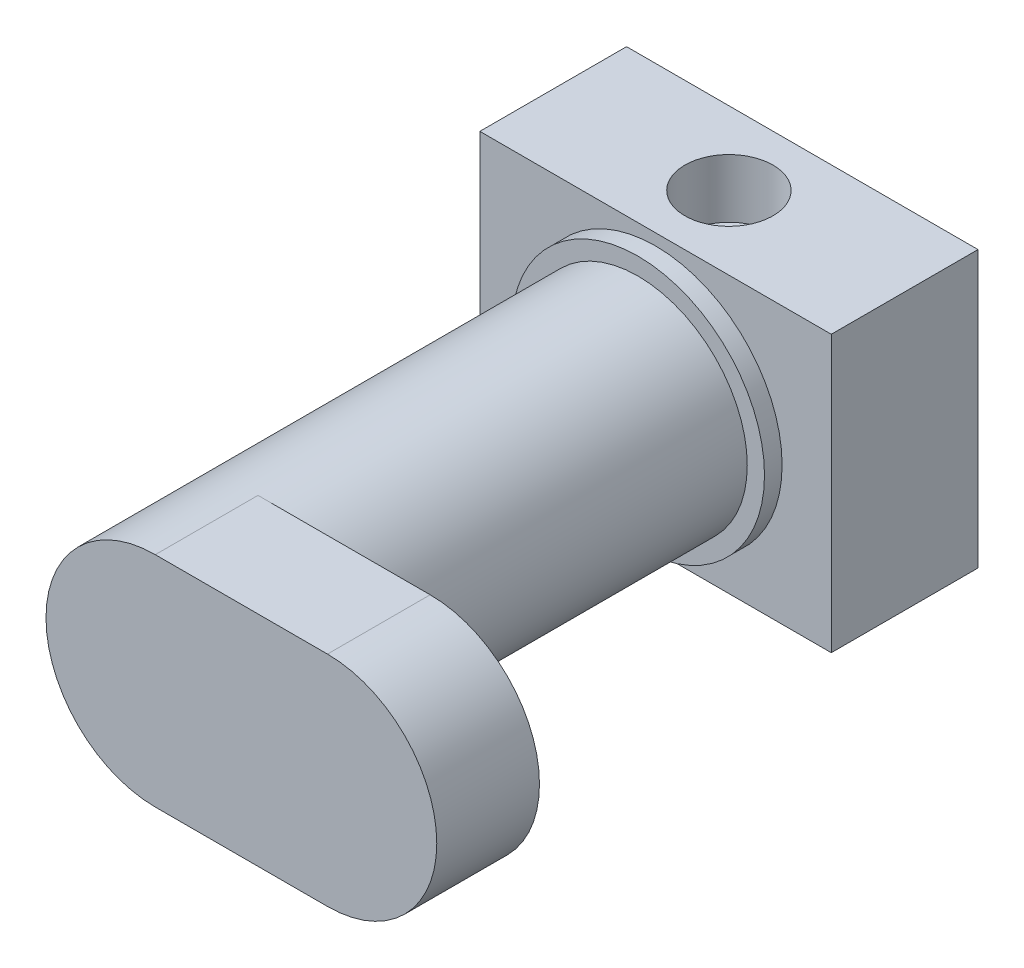
SolidWorks part; units mm, degrees
ref_plane "Front Plane" through (0, 0, 0) normal (0, 0, 1) x (1, 0, 0)
ref_plane "Top Plane" through (0, 0, 0) normal (0, 1, 0) x (1, 0, 0)
ref_plane "Right Plane" through (0, 0, 0) normal (1, 0, 0) x (0, 0, -1)
sketch "Sketch2" plane through (0, 0, 0) normal (0, 0, 1) x (1, 0, 0)
  circle A0 centre (0, 0) radius 17.25
  dimension "D1" = 34.5
extrude "Boss-Extrude1" add sketch "Sketch2" along normal blind 22.4
sketch "Sketch3" plane through (0, 0, 22.4) normal (0, 0, 1) x (1, 0, 0)
  circle A0 centre (0, 0) radius 14.9
  dimension "D1" = 29.8
extrude "Boss-Extrude2" add sketch "Sketch3" along normal blind 38.4
sketch "Sketch4" plane through (0, 0, 60.8) normal (0, 0, 1) x (1, 0, 0)
  circle A0 centre (0, 0) radius 14.9
  dimension "D1" = 29.8
extrude "Boss-Extrude3" add sketch "Sketch4" along normal blind 13.4
sketch "Sketch6" plane through (0, 0, 74.2) normal (0, 0, 1) x (1, 0, 0)
  line L0 (0, 14.9) -> (23.4725, 14.9)
  line L1 (23.4725, -14.9) -> (0, -14.9)
  arc A0 (0, 14.9) -> (0, -14.9) centre (0, 0) ccw
  arc A1 (23.4725, 14.9) -> (23.4725, -14.9) centre (23.4725, 0) cw
extrude "Boss-Extrude4" add sketch "Sketch6" along normal blind 14
sketch "Sketch7" plane through (0, 0, 0) normal (0, 0, -1) x (-1, 0, 0)
  line L0 (-17.25, 0) -> (17.25, 0) construction
  line L1 (0, 17.25) -> (0, -17.25) construction
  line L3 (4, -6) -> (-4, -6)
  line L4 (4, -6) -> (4, 6)
  line L5 (4, 6) -> (-4, 6)
  line L6 (-4, -6) -> (-4, 6)
  line L7 (4, -6) -> (-4, 6) construction
  line L8 (4, 6) -> (-4, -6) construction
  circle A0 centre (0, 0) radius 17.25 construction
  point P7 (0, 0)
  dimension "D1" = 8
  dimension "D2" = 12
extrude "Boss-Extrude5" add sketch "Sketch7" along normal blind 10
sketch "Sketch9" plane through (0, 0, -10) normal (0, 0, -1) x (-1, 0, 0)
  line L1 (1.5, -5) -> (-1.5, -5)
  line L2 (1.5, -5) -> (1.5, 5)
  line L3 (1.5, 5) -> (-1.5, 5)
  line L4 (-1.5, -5) -> (-1.5, 5)
  line L5 (1.5, -5) -> (-1.5, 5) construction
  line L6 (1.5, 5) -> (-1.5, -5) construction
  point P0 (0, 0)
  dimension "D1" = 10
  dimension "D2" = 3
extrude "Cut-Extrude1" cut sketch "Sketch9" against normal blind 2
sketch "Sketch10" plane through (0, 0, 0) normal (0, 0, -1) x (-1, 0, 0)
  line L1 (23.9555, -18.7997) -> (-23.9555, -18.7997)
  line L2 (23.9555, -18.7997) -> (23.9555, 18.7997)
  line L3 (23.9555, 18.7997) -> (-23.9555, 18.7997)
  line L4 (-23.9555, -18.7997) -> (-23.9555, 18.7997)
  line L5 (23.9555, -18.7997) -> (-23.9555, 18.7997) construction
  line L6 (23.9555, 18.7997) -> (-23.9555, -18.7997) construction
  point P0 (0, 0)
extrude "Boss-Extrude6" add sketch "Sketch10" against normal blind 20
ref_plane "Plane1" through (0, 0, 0) normal (0, -1, 0) x (-1, 0, 0)
sketch "Sketch12" plane through (0, -18.7997, 0) normal (0, -1, 0) x (1, 0, 0)
  line L0 (0, 20) -> (0, 0) construction
  line L1 (23.9555, 20) -> (-23.9555, 20) construction
  line L2 (-23.9555, 10) -> (23.9555, 10) construction
  line L3 (-23.9555, 20) -> (-23.9555, 0) construction
  line L4 (23.9555, 20) -> (23.9555, 0) construction
  circle A0 centre (0, 10) radius 6
  dimension "D1" = 12
extrude "Cut-Extrude2" cut sketch "Sketch12" against normal blind 8
mirror "Mirror1" about plane through (0, 0, 0) normal (0, -1, 0) of "Cut-Extrude2"
